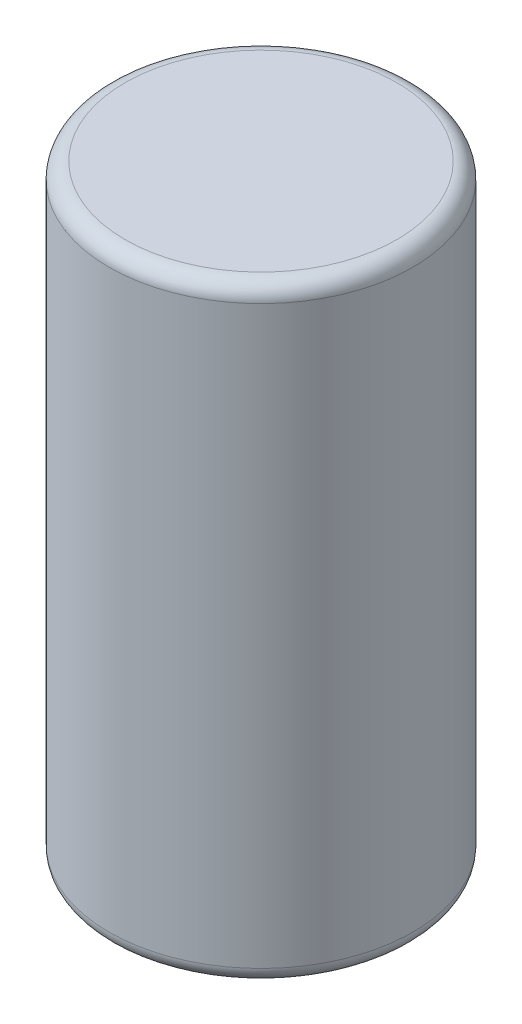
SolidWorks part; units mm, degrees
ref_plane "前视基准面" through (0, 0, 0) normal (0, 0, 1) x (1, 0, 0)
ref_plane "上视基准面" through (0, 0, 0) normal (0, 1, 0) x (1, 0, 0)
ref_plane "右视基准面" through (0, 0, 0) normal (1, 0, 0) x (0, 0, -1)
other "Configuration Table"
sketch "草图1" plane through (0, 0, 0) normal (0, 1, 0) x (1, 0, 0)
  circle A0 centre (0, 0) radius 9.5
  dimension "D1" = 19
extrude "凸台-拉伸1" add sketch "草图1" along normal blind 38
fillet "圆角1" radius 1 2 edges at (0, 0, 9.5) (0, 38, 9.5)
